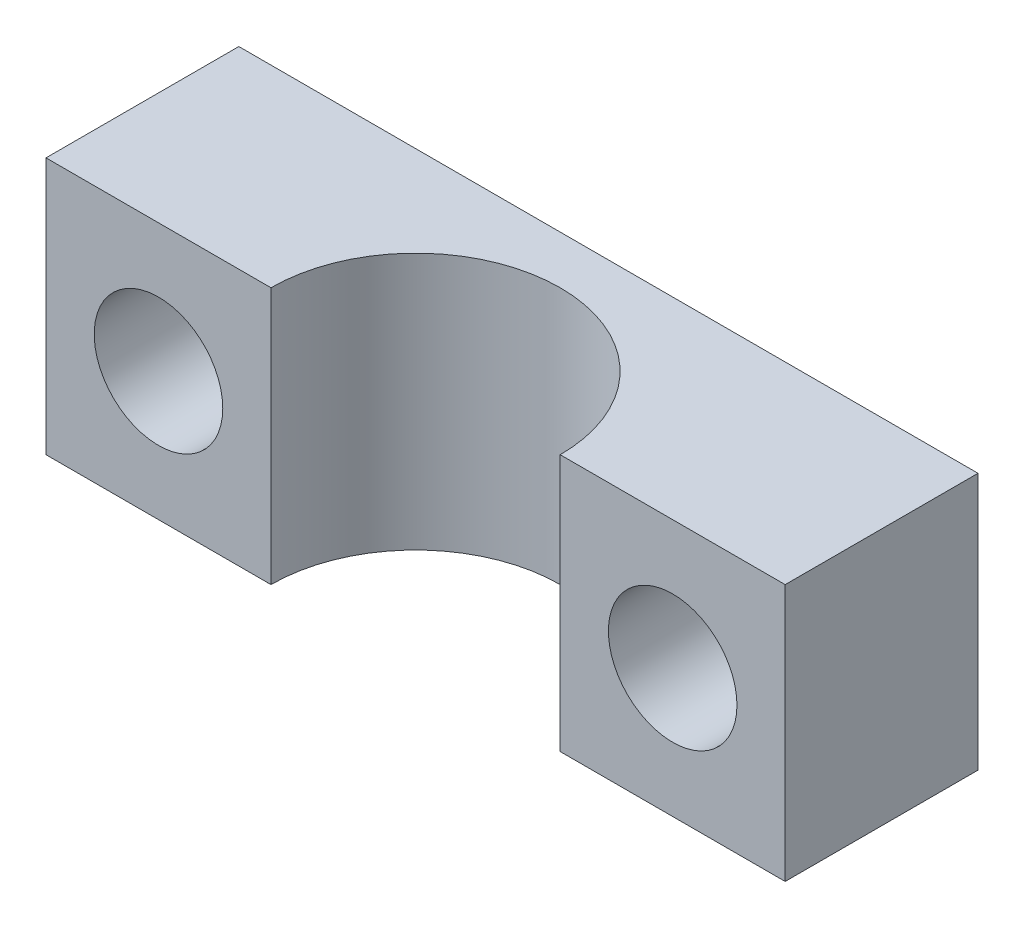
SolidWorks part; units mm, degrees
ref_plane "Front Plane" through (0, 0, 0) normal (0, 0, 1) x (1, 0, 0)
ref_plane "Top Plane" through (0, 0, 0) normal (0, 1, 0) x (1, 0, 0)
ref_plane "Right Plane" through (0, 0, 0) normal (1, 0, 0) x (0, 0, -1)
sketch "Sketch2" plane through (0, 0, 0) normal (0, 0, 1) x (1, 0, 0)
  line L1 (-59.6296, 43.5053) -> (55.3704, 43.5053)
  line L2 (-59.6296, 43.5053) -> (-59.6296, 3.5053)
  line L3 (-59.6296, 3.5053) -> (55.3704, 3.5053)
  line L4 (55.3704, 43.5053) -> (55.3704, 3.5053)
  dimension "D1" = 115
  dimension "D2" = 40
extrude "Boss-Extrude1" add sketch "Sketch2" along normal blind 60
sketch "Sketch3" plane through (0, 43.5053, 0) normal (0, 1, 0) x (1, 0, 0)
  line L0 (-59.6296, -60) -> (-59.6296, 0) construction
  line L1 (-59.6296, -30) -> (-24.6296, -30)
  line L2 (-59.6296, -30) -> (-59.6296, -60)
  line L3 (-59.6296, -60) -> (55.3704, -60)
  line L4 (55.3704, -30) -> (55.3704, -60)
  line L5 (20.3704, -30) -> (55.3704, -30)
  arc A0 (20.3704, -30) -> (-24.6296, -30) centre (-2.1296, -30) ccw
  dimension "D1" = 35
  dimension "D3" = 22.5
  dimension "D2" = 35
  dimension "D4" = 45
extrude "Cut-Extrude1" cut sketch "Sketch3" against normal blind 60
sketch "Sketch4" plane through (0, 0, 30) normal (0, 0, 1) x (1, 0, 0)
  line L0 (-24.6296, 3.5053) -> (-59.6296, 3.5053) construction
  line L1 (-59.6296, 3.5053) -> (-59.6296, 43.5053) construction
  line L2 (55.3704, 3.5053) -> (55.3704, 43.5053) construction
  line L3 (55.3704, 3.5053) -> (20.3704, 3.5053) construction
  circle A0 centre (-42.1296, 23.5053) radius 10
  circle A1 centre (37.8704, 23.5053) radius 10
  dimension "D1" = 20
  dimension "D3" = 17.5
  dimension "D2" = 17.5
  dimension "D4" = 20
  dimension "D5" = 80
extrude "Cut-Extrude2" cut sketch "Sketch4" against normal blind 60
